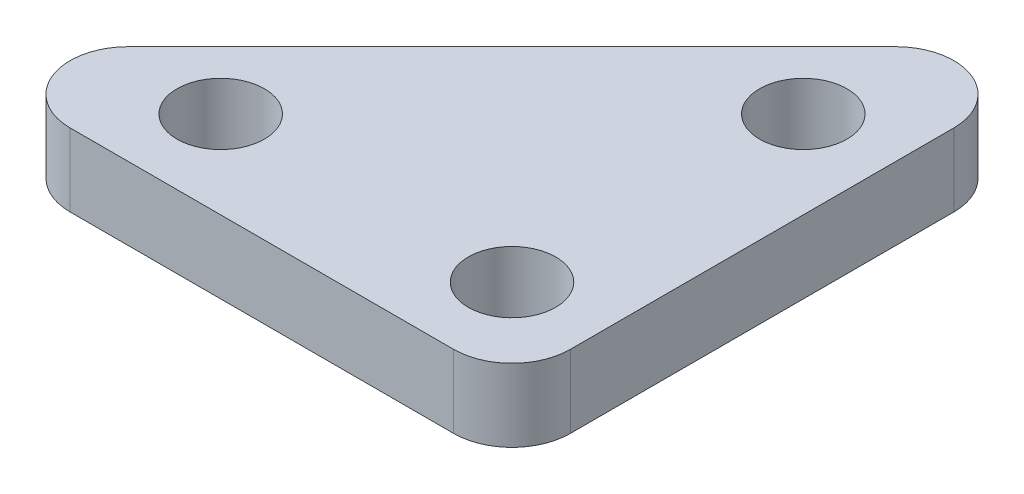
SolidWorks part; units mm, degrees
ref_plane "前视" through (0, 0, 0) normal (0, 0, 1) x (1, 0, 0)
ref_plane "上视" through (0, 0, 0) normal (0, 1, 0) x (1, 0, 0)
ref_plane "右视" through (0, 0, 0) normal (1, 0, 0) x (0, 0, -1)
sketch "Sketch1" plane through (0, 0, 0) normal (0, 1, 0) x (1, 0, 0)
  line L0 (-1.0435, 6.5198) -> (-1.0435, -13.4802)
  line L1 (-1.0435, -13.4802) -> (-21.0435, -13.4802)
  line L2 (-21.0435, -13.4802) -> (-1.0435, 6.5198)
  dimension "D1" = 20
  dimension "D2" = 20
extrude "Boss-Extrude1" add sketch "Sketch1" along normal blind 2.5
fillet "Fillet1" radius 2 3 edges at (-1.0435, 1.25, 13.4802) (-21.0435, 1.25, 13.4802) (-1.0435, 1.25, -6.5198)
sketch "Sketch2" plane through (0, 2.5, 0) normal (0, 1, 0) x (1, 0, 0)
  line L0 (-1.0435, -11.4802) -> (-1.0435, 1.6914) construction
  line L1 (-16.2151, -13.4802) -> (-3.0435, -13.4802) construction
  circle A0 centre (-4.0435, -0.4802) radius 1.5
  circle A1 centre (-4.0435, -10.4802) radius 1.5
  circle A2 centre (-14.0435, -10.4802) radius 1.5
  dimension "D1" = 10
  dimension "D2" = 10
  dimension "D3" = 3
  dimension "D4" = 3
extrude "Cut-Extrude1" cut sketch "Sketch2" against normal through all
